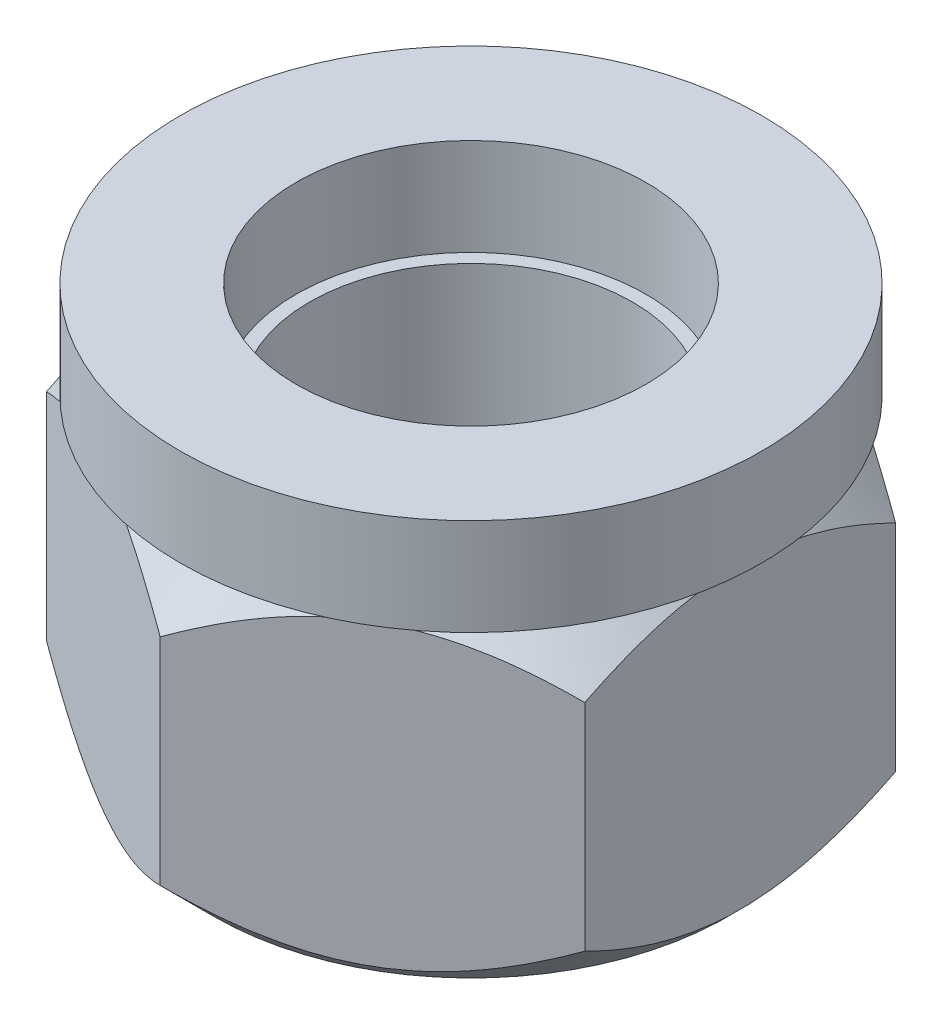
SolidWorks part; units mm, degrees
material "1.0553 (S355J0)"
ref_plane "Płaszczyzna przednia" through (0, 0, 0) normal (0, 0, 1) x (1, 0, 0)
ref_plane "Płaszczyzna górna" through (0, 0, 0) normal (0, 1, 0) x (1, 0, 0)
ref_plane "Płaszczyzna prawa" through (0, 0, 0) normal (1, 0, 0) x (0, 0, -1)
sketch "Szkic1" plane through (0, 0, 0) normal (0, 1, 0) x (1, 0, 0)
  line L1 (5, -2.8868) -> (5, 2.8868)
  line L2 (5, 2.8868) -> (0, 5.7735)
  line L3 (0, 5.7735) -> (-5, 2.8868)
  line L4 (-5, 2.8868) -> (-5, -2.8868)
  line L5 (-5, -2.8868) -> (0, -5.7735)
  line L6 (0, -5.7735) -> (5, -2.8868)
  circle A0 centre (0, 0) radius 5 construction
  circle A1 centre (0, 0) radius 3
  dimension "D1" = 10
  dimension "D2" = 6
extrude "Dodanie-wyciągnięcie1" add sketch "Szkic1" along normal mid plane 6
sketch "Szkic3" plane through (0, 0, 0) normal (1, 0, 0) x (0, 0, -1)
  line L0 (5.7735, 3) -> (5.7735, 2)
  line L1 (5.7735, 3) -> (5.7735, -3) construction
  line L2 (5.7735, 2) -> (4.7735, 3)
  line L3 (2.8868, 3) -> (5.7735, 3) construction
  line L4 (4.7735, 3) -> (5.7735, 3)
  line L5 (0, 0) -> (-12.8095, 0) construction
  line L6 (4.7735, -3) -> (5.7735, -3)
  line L7 (5.7735, -2) -> (4.7735, -3)
  line L8 (5.7735, -3) -> (5.7735, -2)
  line L9 (0, 0) -> (0, 8.5312) construction
  dimension "D1" = 45
  dimension "D2" = 1
revolve "Wycięcie-obrót9" cut sketch "Szkic3" angle 360 about L9
sketch "Szkic4" plane through (0, 3, 0) normal (0, 1, 0) x (1, 0, 0)
  circle A0 centre (0, 0) radius 3.25
  circle A1 centre (0, 0) radius 5.4
  dimension "D1" = 6.5
  dimension "D2" = 10.8
extrude "Dodanie-wyciągnięcie2" add sketch "Szkic4" along normal blind 1.8
